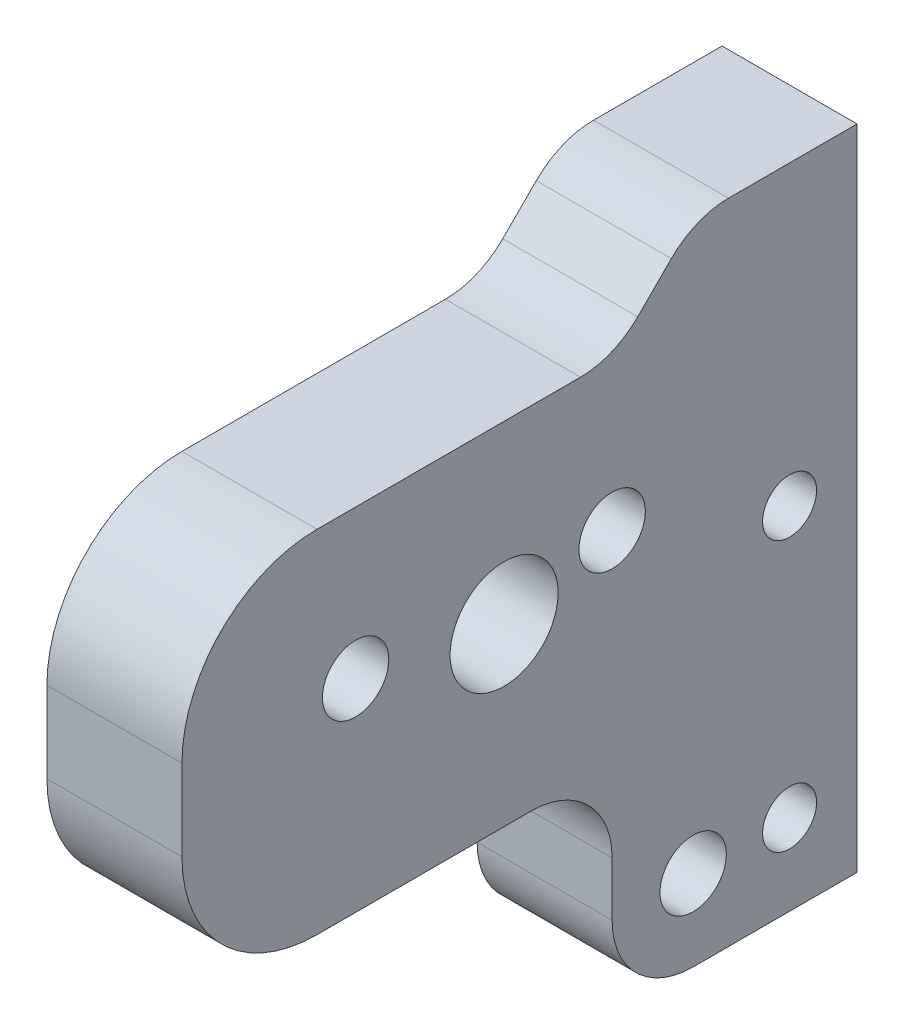
SolidWorks part; units mm, degrees
ref_plane "Front Plane" through (0, 0, 0) normal (1, 0, 0) x (0, 1, 0)
ref_plane "Top Plane" through (0, 0, 0) normal (0, 0, 1) x (0, 1, 0)
ref_plane "Right Plane" through (0, 0, 0) normal (0, 1, 0) x (-1, 0, 0)
sketch "Sketch1" plane through (0, 0, 0) normal (1, 0, 0) x (0, 1, 0)
  line L0 (-11.7291, -13.4323) -> (-11.7291, -7.3623)
  line L1 (-8.7291, -4.3623) -> (-6.7291, -4.3623)
  line L2 (-3.7291, -1.3623) -> (-3.7291, 11.5677)
  line L4 (9.2709, 8.5677) -> (9.2709, -3.1896)
  line L5 (11.3922, -6.5536) -> (10.1495, -5.311)
  line L6 (12.2709, -8.6749) -> (12.2709, -13.4323)
  line L7 (12.2709, -13.4323) -> (-11.7291, -13.4323)
  line L8 (3.7709, -4.3623) -> (3.7709, 5.1377) construction
  line L9 (3.7709, 0.3877) -> (-3.7291, 0.3877) construction
  line L10 (-3.7291, 11.5677) -> (9.2709, 11.5677)
  line L11 (9.2709, 11.5677) -> (9.2709, 8.5677)
  arc A0 (-8.7291, -4.3623) -> (-11.7291, -7.3623) centre (-8.7291, -7.3623) ccw
  arc A1 (-6.7291, -4.3623) -> (-3.7291, -1.3623) centre (-6.7291, -1.3623) ccw
  arc A4 (9.2709, -3.1896) -> (10.1495, -5.311) centre (12.2709, -3.1896) ccw
  arc A5 (12.2709, -8.6749) -> (11.3922, -6.5536) centre (9.2709, -8.6749) ccw
  circle A6 centre (3.7709, 5.1377) radius 1.2295
  circle A7 centre (2.7709, -0.3623) radius 2
  circle A8 centre (3.7709, -4.3623) radius 1.2295
  circle A9 centre (-8.7291, -7.3623) radius 1.2295
  circle A10 centre (-8.7291, -10.9323) radius 1
  circle A11 centre (1.2709, -10.9323) radius 1
  dimension "D1" = 7.5
  dimension "D2" = 9.5
  dimension "D3" = 90
  dimension "D4" = 13.07
  dimension "D5" = 13.82
extrude "Boss-Extrude1" add sketch "Sketch1" along normal blind 5
sketch "Sketch2" plane through (0, 0, -13.4323) normal (0, 0, -1) x (1, 0, 0)
  line L0 (5, -12.2709) -> (0, -12.2709) construction
  line L1 (5, 11.7291) -> (5, -12.2709) construction
  circle A0 centre (2.5, -8.7709) radius 1.25
  circle A1 centre (2.5, 5.2291) radius 1.25
  dimension "D1" = 2.5
  dimension "D2" = 2.5
  dimension "D4" = 14
  dimension "D5" = 2.5
  dimension "D6" = 2.5
  dimension "D3" = 3.5
extrude "Cut-Extrude1" cut sketch "Sketch2" against normal blind 5
fillet "Fillet1" radius 5 2 edges at (2.5, 9.2709, 11.5677) (2.5, -3.7291, 11.5677)
